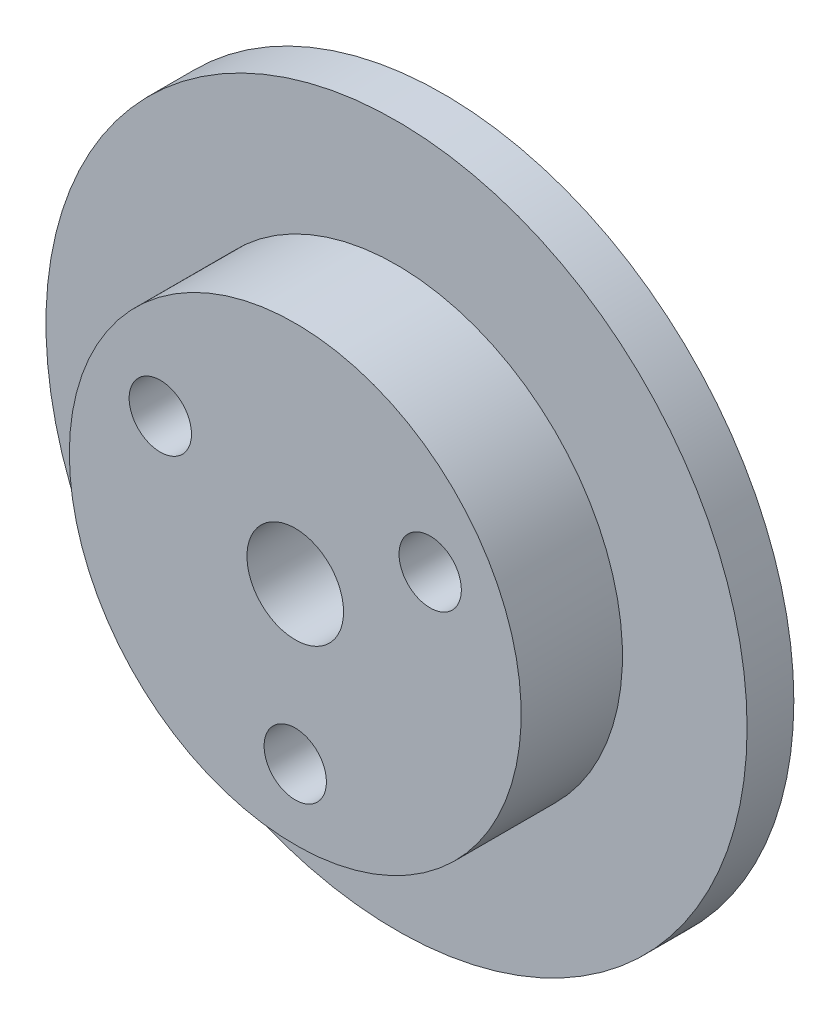
SolidWorks part; units mm, degrees
ref_plane "Plan de face" through (0, 0, 0) normal (0, 0, 1) x (1, 0, 0)
ref_plane "Plan de dessus" through (0, 0, 0) normal (0, 1, 0) x (1, 0, 0)
ref_plane "Plan de droite" through (0, 0, 0) normal (1, 0, 0) x (0, 0, -1)
sketch "Esquisse1" plane through (0, 0, 0) normal (0, 0, 1) x (1, 0, 0)
  line L0 (0, 0) -> (-45.0658, 26.0187) construction
  line L1 (0, 0) -> (42.4756, 24.5233) construction
  line L2 (0, 0) -> (0, -54.477) construction
  circle A0 centre (0, 0) radius 14.5 construction
  circle A1 centre (0, 0) radius 22.5
  circle A3 centre (0, 0) radius 10 construction
  dimension "D1" = 120
  dimension "D2" = 120
extrude "Boss.-Extru.1" add sketch "Esquisse1" along normal blind 3
sketch "Esquisse2" plane through (0, 0, 3) normal (0, 0, 1) x (1, 0, 0)
  circle A0 centre (0, 0) radius 14.5
extrude "Boss.-Extru.2" add sketch "Esquisse2" along normal blind 6.5
sketch "Esquisse3" plane through (0, 0, 9.5) normal (0, 0, 1) x (1, 0, 0)
  line L0 (0, 0) -> (42.4756, 24.5233) construction
  line L1 (0, 0) -> (-45.0658, 26.0187) construction
  line L2 (0, 0) -> (0, -54.477) construction
  circle A0 centre (8.6603, 5) radius 2
  circle A1 centre (0, 0) radius 10 construction
  circle A2 centre (-8.6603, 5) radius 2
  circle A3 centre (0, -10) radius 2
  circle A4 centre (0, 0) radius 3.1
extrude "Enlèv. mat.-Extru.1" cut sketch "Esquisse3" against normal through all
